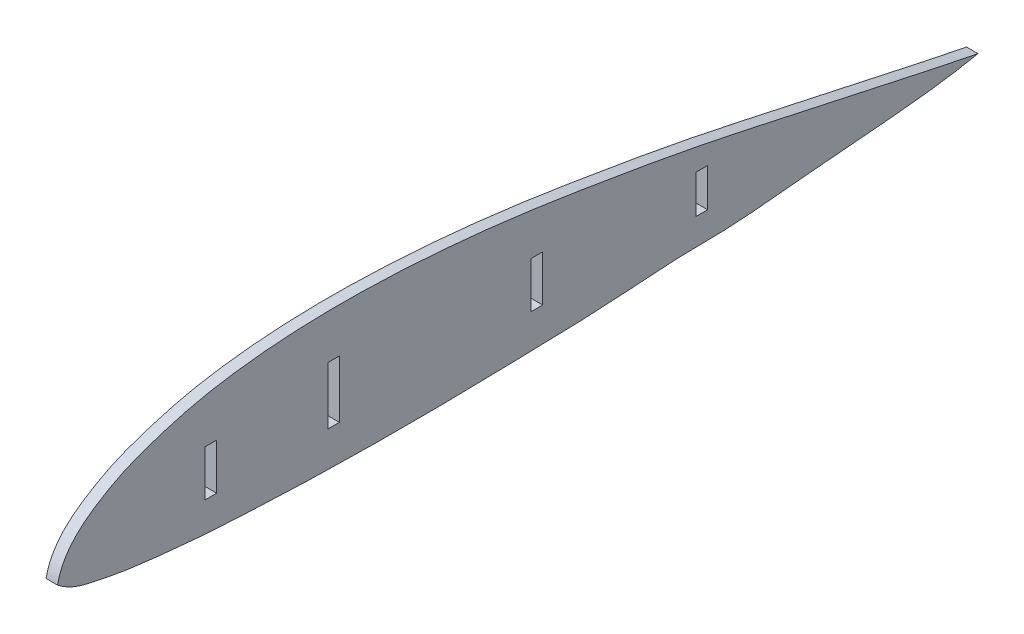
SolidWorks part; units mm, degrees
ref_plane "Спереди" through (0, 0, 0) normal (0, 0, 1) x (1, 0, 0)
ref_plane "Сверху" through (0, 0, 0) normal (0, 1, 0) x (1, 0, 0)
ref_plane "Справа" through (0, 0, 0) normal (1, 0, 0) x (0, 0, -1)
sketch "Эскиз1" plane through (0, 0, 0) normal (1, 0, 0) x (0, 0, -1)
  spline S0 degree 3 poles (-240, 0) (-238.5396, 6.886) (-231.612, 12.3378) (-222.1753, 17.4121) (-214.1119, 20.3435) (-204.1561, 23.2639) (-188.1046, 25.8933) (-168.0072, 26.9601) (-143.9456, 26.0264) (-119.9183, 23.5678) (-95.9538, 19.7588) (-71.9127, 15.562) (-48.006, 10.2206) (-23.9898, 5.1714) (-8.0375, 1.5236) (0, 0) knots 0 0 0 0 0.075346 0.102328 0.12789 0.177564 0.226025 0.321727 0.4173 0.513305 0.60992 0.706974 0.804635 0.902346 1 1 1 1
  spline S1 degree 3 poles (-240, 0) (-236.5239, -2.8866) (-230.2208, -4.0678) (-222.0286, -5.6488) (-214.0096, -6.6085) (-204.0195, -7.6506) (-188.0105, -8.621) (-168.0084, -9.355) (-143.9974, -9.5447) (-119.9964, -9.0006) (-95.9841, -8.4523) (-79.4445, -6.8615) (-63.4129, -6.9414) (-47.4215, -5.1493) (-23.952, -3.3462) (-7.916, -1.6722) (0, 0) knots 0 0 0 0 0.053475 0.078709 0.103753 0.153673 0.203448 0.302856 0.402199 0.501554 0.600955 0.70043 0.70748 0.799996 0.899716 1 1 1 1
  point P0 (-240, 0)
  point P1 (-234, 9.888)
  point P2 (-228, 14.16)
  point P3 (-222, 17.316)
  point P4 (-216, 19.608)
  point P5 (-204, 23.04)
  point P6 (-192, 25.104)
  point P7 (-168, 26.592)
  point P8 (-144, 25.776)
  point P9 (-120, 23.352)
  point P10 (-96, 19.704)
  point P11 (-72, 15.384)
  point P12 (-48, 10.272)
  point P13 (-24, 5.1)
  point P14 (-12, 2.46)
  point P15 (0, 0)
  point P16 (-234, -3.12)
  point P17 (-228, -4.5)
  point P18 (-222, -5.58)
  point P19 (-216, -6.36)
  point P20 (-204, -7.5648)
  point P21 (-192, -8.3472)
  point P22 (-168, -9.24)
  point P23 (-144, -9.4224)
  point P24 (-120, -9)
  point P25 (-96, -8.16)
  point P26 (-72, -6.9024)
  point P27 (-48, -5.34)
  point P28 (-24, -3.24)
  point P29 (-12, -1.98)
extrude "Бобышка-Вытянуть1" add sketch "Эскиз1" along normal blind 3
sketch "Эскиз2" plane through (0, 0, 0) normal (-1, 0, 0) x (0, 0, 1)
  line L0 (116.5, 0) -> (116.5, 12)
  line L2 (116.5, 12) -> (113.5, 12)
  line L7 (201.5, 0) -> (198.5, 0)
  line L8 (116.5, 0) -> (113.5, 0)
  line L9 (113.5, 12) -> (113.5, 0)
  line L10 (198.5, 0) -> (198.5, 12)
  line L11 (198.5, 12) -> (201.5, 12)
  line L12 (201.5, 12) -> (201.5, 0)
  line L13 (169.5, 0) -> (169.5, 15)
  line L14 (169.5, 15) -> (166.5, 15)
  line L15 (166.5, 0) -> (169.5, 0)
  line L16 (166.5, 15) -> (166.5, 0)
  line L17 (70.5, 0) -> (70.5, 10)
  line L18 (70.5, 0) -> (73.5, 0)
  line L19 (70.5, 10) -> (73.5, 10)
  line L20 (73.5, 10) -> (73.5, 0)
  dimension "D1" = 70.5
  dimension "D2" = 10
  dimension "D3" = 12
  dimension "D4" = 15
  dimension "D5" = 12
  dimension "D6" = 113.5
  dimension "D7" = 166.5
  dimension "D8" = 198.5
extrude "Вырез-Вытянуть1" cut sketch "Эскиз2" against normal blind 3
